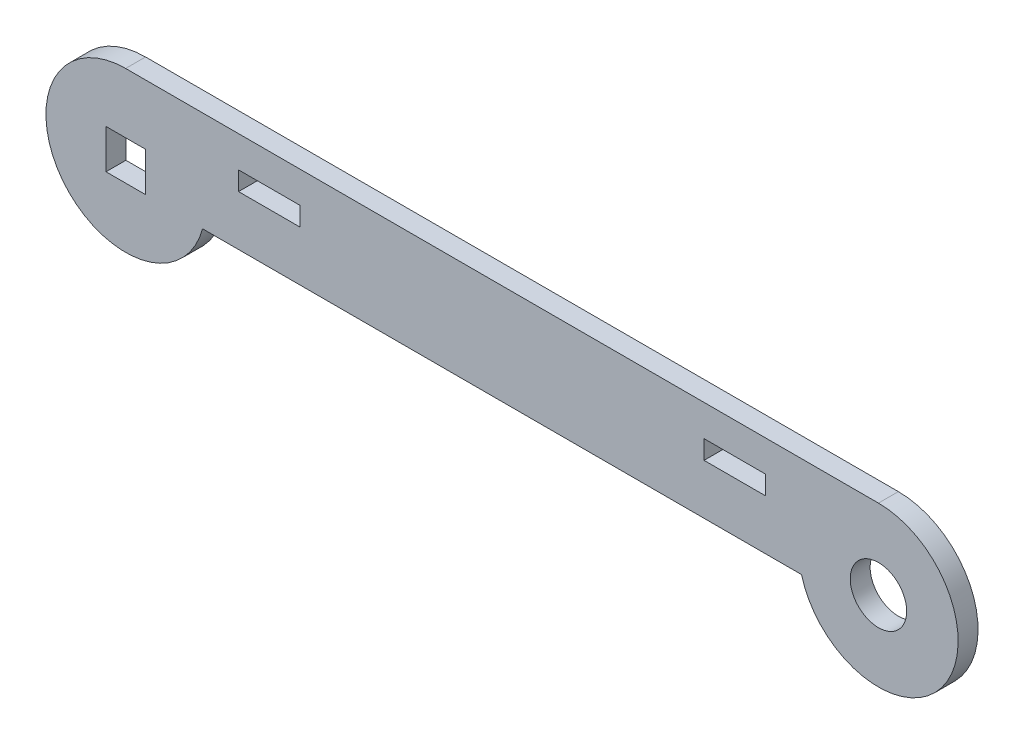
SolidWorks part; units mm, degrees
material "Acrylic (Medium-high impact)"
ref_plane "Front Plane" through (0, 0, 0) normal (0, 0, 1) x (1, 0, 0)
ref_plane "Top Plane" through (0, 0, 0) normal (0, 1, 0) x (1, 0, 0)
ref_plane "Right Plane" through (0, 0, 0) normal (1, 0, 0) x (0, 0, -1)
sketch "Sketch1" plane through (0, 0, 0) normal (0, 0, 1) x (1, 0, 0)
  line L0 (0, 0) -> (60, 0) construction
  line L1 (-1.565, -1.565) -> (1.565, -1.565)
  line L2 (-1.565, -1.565) -> (-1.565, 1.565)
  line L3 (-1.565, 1.565) -> (1.565, 1.565)
  line L4 (1.565, -1.565) -> (1.565, 1.565)
  line L5 (-1.565, -1.565) -> (1.565, 1.565) construction
  line L6 (-1.565, 1.565) -> (1.565, -1.565) construction
  line L7 (0, 6.35) -> (60, 6.35)
  line L8 (6.1319, -1.65) -> (53.8681, -1.65)
  line L9 (30, 6.35) -> (30, -1.65) construction
  line L10 (9, 2.35) -> (13.9, 2.35)
  line L11 (9, 2.35) -> (9, 3.85)
  line L12 (9, 3.85) -> (13.9, 3.85)
  line L13 (13.9, 2.35) -> (13.9, 3.85)
  line L14 (51, 2.35) -> (46.1, 2.35)
  line L15 (46.1, 2.35) -> (46.1, 3.85)
  line L16 (51, 2.35) -> (51, 3.85)
  line L17 (51, 3.85) -> (46.1, 3.85)
  circle A0 centre (0, 0) radius 6.35
  circle A1 centre (60, 0) radius 6.35
  circle A2 centre (60, 0) radius 2.25
  circle A3 centre (0, 0) radius 8 construction
  dimension "D4" = 4.5
  dimension "D6" = 1.5
  dimension "D8" = 16
  dimension "D2" = 3.13
  dimension "D3" = 3.13
  dimension "D1" = 60
  dimension "D5" = 8
  dimension "D7" = 4.9
  dimension "D9" = 2.5
  dimension "D10" = 9
extrude "Boss-Extrude1" add sketch "Sketch1" along normal blind 1.5875
